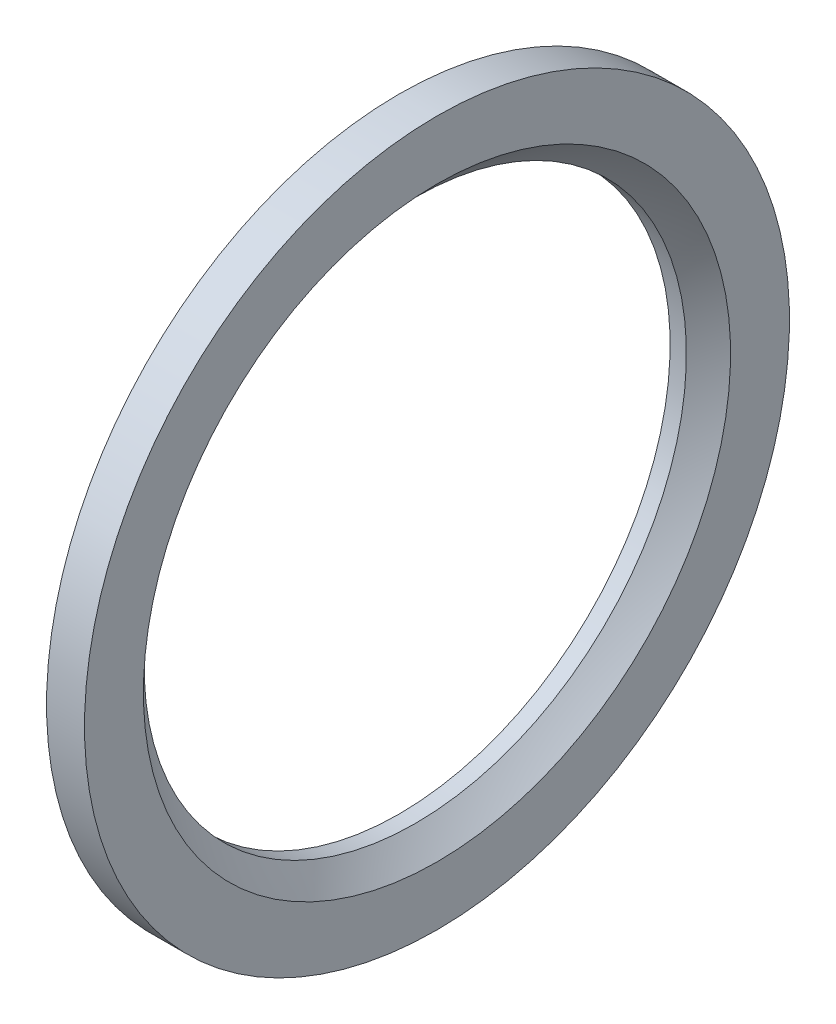
SolidWorks part; units mm, degrees
material "PTFE (general)"
ref_plane "Front Plane" through (0, 0, 0) normal (0, 0, 1) x (1, 0, 0)
ref_plane "Top Plane" through (0, 0, 0) normal (0, 1, 0) x (1, 0, 0)
ref_plane "Right Plane" through (0, 0, 0) normal (1, 0, 0) x (0, 0, -1)
sketch "Sketch1" plane through (0, 0, 0) normal (0, 0, 1) x (1, 0, 0)
  line L0 (0, 0) -> (7.4805, 0) construction
  line L1 (0.381, 6.35) -> (0, 6.35)
  line L2 (0, 6.35) -> (0, 8.255)
  line L4 (0, 0) -> (0, 6.35) construction
  line L5 (0.889, 6.8759) -> (0.889, 8.255)
  line L6 (0.889, 8.255) -> (0, 8.255)
  arc A0 (0.381, 6.35) -> (0.889, 6.8759) centre (7.4805, 0) cw
  point P5 (0.8821, 5.4798)
  point P9 (0, 5.5732)
  point P10 (0, 0)
  point P11 (0, 5.5615)
  point P12 (0, 6.0523)
  point P13 (0.889, 5.6316)
  point P14 (0, 0)
  point P15 (0, 0)
  dimension "D1" = 9.525
  dimension "D2" = 12.7
  dimension "D3" = 0.889
  dimension "D4" = 0.381
  dimension "D5" = 16.51
revolve "Revolve1" add sketch "Sketch1" angle 360 about L0
